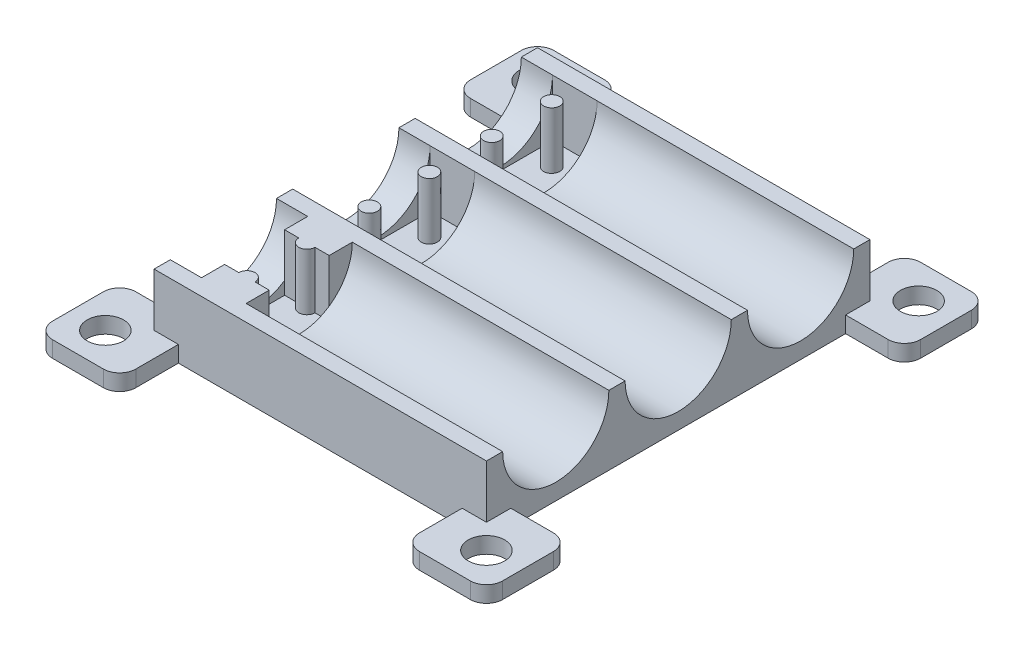
SolidWorks part; units mm, degrees
ref_plane "Front Plane" through (0, 0, 0) normal (0, 0, 1) x (1, 0, 0)
ref_plane "Top Plane" through (0, 0, 0) normal (0, 1, 0) x (1, 0, 0)
ref_plane "Right Plane" through (0, 0, 0) normal (1, 0, 0) x (0, 0, -1)
sketch "Sketch1" plane through (0, 0, 0) normal (1, 0, 0) x (0, 0, -1)
  line L0 (-8.55, 0) -> (-6.55, 0)
  line L1 (-6.55, 0) -> (6.55, 0) construction
  line L2 (6.55, 0) -> (8.55, 0)
  line L3 (-21.65, 0) -> (-8.55, 0) construction
  line L4 (8.55, 0) -> (21.65, 0) construction
  line L5 (-21.65, 0) -> (-23.65, 0)
  line L6 (-23.65, 0) -> (-23.65, -8.55)
  line L7 (-23.65, -8.55) -> (23.65, -8.55)
  line L8 (23.65, -8.55) -> (23.65, 0)
  line L9 (23.65, 0) -> (21.65, 0)
  line L10 (0, -6.55) -> (0, -8.55) construction
  arc A0 (-6.55, 0) -> (6.55, 0) centre (0, 0) ccw
  arc A1 (-21.65, 0) -> (-8.55, 0) centre (-15.1, 0) ccw
  arc A2 (8.55, 0) -> (21.65, 0) centre (15.1, 0) ccw
  dimension "D1" = 13.1
  dimension "D2" = 2
extrude "Boss-Extrude1" add sketch "Sketch1" along normal blind 41
sketch "Sketch2" plane through (0, 0, 0) normal (0, 1, 0) x (1, 0, 0)
  line L0 (6.6, -3.7) -> (6.6, 3.7) construction
  line L1 (5.6, -3.7) -> (5.6, 3.7) construction
  line L2 (0, -7.55) -> (41, -7.55) construction
  line L3 (0, -6.55) -> (0, -8.55) construction
  line L4 (41, -6.55) -> (41, -8.55) construction
  line L5 (0, 7.55) -> (41, 7.55) construction
  line L6 (0, 8.55) -> (0, 6.55) construction
  line L7 (41, 8.55) -> (41, 6.55) construction
  circle A2 centre (6.6, 3.7) radius 1
  circle A3 centre (6.6, -3.7) radius 1
  circle A4 centre (6.6, -11.4) radius 1
  circle A5 centre (6.6, -18.8) radius 1
  circle A6 centre (6.6, 18.8) radius 1
  circle A7 centre (6.6, 11.4) radius 1
  point P4 (6.6, 0)
  point P20 (0, 7.55)
  dimension "D2" = 2
  dimension "D1" = 5.6
  dimension "D3" = 7.4
extrude "Boss-Extrude2" add sketch "Sketch2" against normal up to next
sketch "Sketch4" plane through (0, 0, 0) normal (0, 1, 0) x (1, 0, 0)
  line L0 (41, -6.55) -> (0, -6.55) construction
  line L1 (3.85, -6.55) -> (9.35, -6.55)
  line L2 (3.85, -6.55) -> (3.85, 6.55)
  line L3 (3.85, 6.55) -> (9.35, 6.55)
  line L4 (9.35, -6.55) -> (9.35, 6.55)
  line L5 (41, 6.55) -> (0, 6.55) construction
  line L6 (6.6, -3.7) -> (6.6, 3.7) construction
  line L7 (9.35, 0) -> (3.85, 0) construction
  line L8 (0, -7.55) -> (41, -7.55) construction
  line L9 (0, -6.55) -> (0, -8.55) construction
  line L10 (41, -6.55) -> (41, -8.55) construction
  line L11 (0, 7.55) -> (41, 7.55) construction
  line L12 (0, 8.55) -> (0, 6.55) construction
  line L13 (41, 8.55) -> (41, 6.55) construction
  line L14 (3.85, -21.65) -> (9.35, -21.65)
  line L15 (9.35, -8.55) -> (9.35, -21.65)
  line L16 (3.85, -8.55) -> (9.35, -8.55)
  line L17 (3.85, -8.55) -> (3.85, -21.65)
  line L18 (3.85, 8.55) -> (9.35, 8.55)
  line L19 (9.35, 21.65) -> (9.35, 8.55)
  line L20 (3.85, 21.65) -> (9.35, 21.65)
  line L21 (3.85, 21.65) -> (3.85, 8.55)
  circle A0 centre (6.6, 3.7) radius 1 construction
  circle A1 centre (6.6, -3.7) radius 1 construction
  circle A2 centre (6.6, 3.7) radius 1
  circle A3 centre (6.6, -3.7) radius 1
  circle A4 centre (6.6, -11.4) radius 1
  circle A5 centre (6.6, -18.8) radius 1
  circle A6 centre (6.6, 11.4) radius 1
  circle A7 centre (6.6, 18.8) radius 1
  point P16 (6.6, 0)
  point P17 (6.6, 0)
  dimension "D1" = 5.5
extrude "Cut-Extrude1" cut sketch "Sketch4" against normal blind 7
sketch "Sketch5" plane through (0, -8.55, 0) normal (0, -1, 0) x (1, 0, 0)
  line L0 (0, 23.65) -> (0, 20.65)
  line L1 (-5.2552, 30.9052) -> (1, 30.9052)
  line L2 (-7.2552, 28.9052) -> (-7.2552, 22.65)
  line L3 (-5.2552, 20.65) -> (0, 20.65)
  line L12 (3, 28.9052) -> (3, 23.65)
  line L14 (0, 23.65) -> (3, 23.65)
  line L16 (0, 23.65) -> (-7.2552, 30.9052) construction
  line L17 (-3.0052, 28.9052) -> (-3.0052, 30.9052) construction
  line L18 (-1.4142, 25.0642) -> (0, 23.65) construction
  line L19 (0, 0) -> (41, 0) construction
  line L20 (41, 23.65) -> (41, -23.65) construction
  line L21 (-1.4142, -25.0642) -> (0, -23.65) construction
  line L22 (-3.0052, -28.9052) -> (-3.0052, -30.9052) construction
  line L23 (0, -23.65) -> (-7.2552, -30.9052) construction
  line L24 (0, -23.65) -> (3, -23.65)
  line L25 (3, -28.9052) -> (3, -23.65)
  line L26 (-5.2552, -20.65) -> (0, -20.65)
  line L27 (-7.2552, -28.9052) -> (-7.2552, -22.65)
  line L28 (-5.2552, -30.9052) -> (1, -30.9052)
  line L29 (0, -23.65) -> (0, -20.65)
  line L30 (20.5, 23.65) -> (20.5, -23.65) construction
  line L31 (41, 23.65) -> (0, 23.65) construction
  line L32 (41, -23.65) -> (0, -23.65) construction
  line L33 (41, -23.65) -> (48.2552, -30.9052) construction
  line L34 (44.0052, -28.9052) -> (44.0052, -30.9052) construction
  line L35 (42.4142, -25.0642) -> (41, -23.65) construction
  line L36 (42.4142, 25.0642) -> (41, 23.65) construction
  line L37 (44.0052, 28.9052) -> (44.0052, 30.9052) construction
  line L38 (41, 23.65) -> (48.2552, 30.9052) construction
  line L39 (41, -23.65) -> (41, -20.65)
  line L40 (46.2552, -30.9052) -> (40, -30.9052)
  line L41 (48.2552, -28.9052) -> (48.2552, -22.65)
  line L42 (46.2552, -20.65) -> (41, -20.65)
  line L43 (38, -28.9052) -> (38, -23.65)
  line L44 (41, -23.65) -> (38, -23.65)
  line L45 (41, 23.65) -> (38, 23.65)
  line L46 (38, 28.9052) -> (38, 23.65)
  line L47 (46.2552, 20.65) -> (41, 20.65)
  line L48 (48.2552, 28.9052) -> (48.2552, 22.65)
  line L49 (46.2552, 30.9052) -> (40, 30.9052)
  line L50 (41, 23.65) -> (41, 20.65)
  circle A0 centre (-3.0052, 26.6552) radius 2.25
  arc A1 (-7.2552, 22.65) -> (-5.2552, 20.65) centre (-5.2552, 22.65) ccw
  arc A2 (-5.2552, 30.9052) -> (-7.2552, 28.9052) centre (-5.2552, 28.9052) ccw
  arc A3 (1, 30.9052) -> (3, 28.9052) centre (1, 28.9052) cw
  arc A4 (1, -30.9052) -> (3, -28.9052) centre (1, -28.9052) ccw
  arc A5 (-5.2552, -30.9052) -> (-7.2552, -28.9052) centre (-5.2552, -28.9052) cw
  arc A6 (-7.2552, -22.65) -> (-5.2552, -20.65) centre (-5.2552, -22.65) cw
  circle A7 centre (-3.0052, -26.6552) radius 2.25
  circle A8 centre (44.0052, -26.6552) radius 2.25
  arc A9 (48.2552, -22.65) -> (46.2552, -20.65) centre (46.2552, -22.65) ccw
  arc A10 (46.2552, -30.9052) -> (48.2552, -28.9052) centre (46.2552, -28.9052) ccw
  arc A11 (40, -30.9052) -> (38, -28.9052) centre (40, -28.9052) cw
  arc A12 (40, 30.9052) -> (38, 28.9052) centre (40, 28.9052) ccw
  arc A13 (46.2552, 30.9052) -> (48.2552, 28.9052) centre (46.2552, 28.9052) cw
  arc A14 (48.2552, 22.65) -> (46.2552, 20.65) centre (46.2552, 22.65) cw
  circle A15 centre (44.0052, 26.6552) radius 2.25
  dimension "D1" = 4.5
  dimension "D4" = 2
  dimension "D5" = 2
  dimension "D2" = 3
  dimension "D3" = 2
extrude "Boss-Extrude3" add sketch "Sketch5" against normal blind 2
sketch "Sketch6" plane through (0, 0, 0) normal (0, 1, 0) x (1, 0, 0)
  line L0 (0, 0) -> (41, 0) construction
  line L1 (3.85, -3.7) -> (9.35, -3.7)
  line L2 (9.35, -3.7) -> (9.35, -6.55)
  line L3 (9.35, -6.55) -> (3.85, -6.55)
  line L4 (3.85, -6.55) -> (3.85, -3.7)
  line L5 (7.6, -3.7) -> (5.6, -3.7) construction
  line L6 (7.6, 3.7) -> (5.6, 3.7) construction
  line L7 (3.85, 6.55) -> (3.85, 3.7)
  line L8 (9.35, 6.55) -> (3.85, 6.55)
  line L9 (9.35, 3.7) -> (9.35, 6.55)
  line L10 (3.85, 3.7) -> (9.35, 3.7)
  line L11 (0, -7.55) -> (41, -7.55) construction
  line L12 (0, 7.55) -> (41, 7.55) construction
  line L13 (0, -6.55) -> (0, -8.55) construction
  line L14 (0, 8.55) -> (0, 6.55) construction
  line L15 (41, 8.55) -> (41, 6.55) construction
  line L16 (41, -6.55) -> (41, 6.55) construction
  line L17 (41, -6.55) -> (41, -8.55) construction
  line L18 (9.35, -6.55) -> (9.35, 6.55) construction
  line L19 (5.6, -3.7) -> (7.6, -3.7) construction
  line L20 (5.6, -11.4) -> (7.6, -11.4) construction
  line L21 (7.6, -18.8) -> (5.6, -18.8) construction
  line L22 (7.6, -11.4) -> (5.6, -11.4) construction
  line L23 (3.85, -18.8) -> (9.35, -18.8)
  line L24 (9.35, -18.8) -> (9.35, -21.65)
  line L25 (9.35, -21.65) -> (3.85, -21.65)
  line L26 (3.85, -21.65) -> (3.85, -18.8)
  line L27 (3.85, -8.55) -> (3.85, -11.4)
  line L28 (9.35, -8.55) -> (3.85, -8.55)
  line L29 (9.35, -11.4) -> (9.35, -8.55)
  line L30 (3.85, -11.4) -> (9.35, -11.4)
  line L31 (5.6, 18.8) -> (7.6, 18.8) construction
  line L32 (7.6, 11.4) -> (5.6, 11.4) construction
  line L33 (7.6, 18.8) -> (5.6, 18.8) construction
  line L34 (3.85, 11.4) -> (9.35, 11.4)
  line L35 (9.35, 11.4) -> (9.35, 8.55)
  line L36 (9.35, 8.55) -> (3.85, 8.55)
  line L37 (3.85, 8.55) -> (3.85, 11.4)
  line L38 (3.85, 21.65) -> (3.85, 18.8)
  line L39 (9.35, 21.65) -> (3.85, 21.65)
  line L40 (9.35, 18.8) -> (9.35, 21.65)
  line L41 (3.85, 18.8) -> (9.35, 18.8)
  circle A0 centre (6.6, -3.7) radius 1 construction
  circle A1 centre (6.6, -3.7) radius 1 construction
extrude "Boss-Extrude4" add sketch "Sketch6" against normal up to surface (7 mm away) up to face at (6.6, -7, -19.8)
sketch "Sketch7" plane through (0, 0, 0) normal (0, 1, 0) x (1, 0, 0)
  line L0 (5.6, 3.7) -> (3.85, 3.7)
  line L1 (3.85, 3.7) -> (3.85, 6.55)
  line L2 (3.85, 6.55) -> (9.35, 6.55)
  line L3 (9.35, 6.55) -> (9.35, 3.7)
  line L4 (7.6, 3.7) -> (9.35, 3.7) construction
  line L5 (7.6, 3.7) -> (9.35, 3.7)
  line L6 (0, 0) -> (41, 0) construction
  line L7 (41, -6.55) -> (41, 6.55) construction
  line L8 (7.6, -3.7) -> (9.35, -3.7)
  line L9 (9.35, -6.55) -> (9.35, -3.7)
  line L10 (3.85, -6.55) -> (9.35, -6.55)
  line L11 (3.85, -3.7) -> (3.85, -6.55)
  line L12 (5.6, -3.7) -> (3.85, -3.7)
  line L13 (0, 7.55) -> (41, 7.55) construction
  line L14 (0, 8.55) -> (0, 6.55) construction
  line L15 (41, 8.55) -> (41, 6.55) construction
  line L16 (5.6, 18.8) -> (3.85, 18.8)
  line L17 (3.85, 18.8) -> (3.85, 21.65)
  line L18 (3.85, 21.65) -> (9.35, 21.65)
  line L19 (9.35, 21.65) -> (9.35, 18.8)
  line L20 (7.6, 18.8) -> (9.35, 18.8)
  line L21 (7.6, 11.4) -> (9.35, 11.4)
  line L22 (9.35, 8.55) -> (9.35, 11.4)
  line L23 (3.85, 8.55) -> (9.35, 8.55)
  line L24 (3.85, 11.4) -> (3.85, 8.55)
  line L25 (5.6, 11.4) -> (3.85, 11.4)
  arc A0 (7.6, 3.7) -> (5.6, 3.7) centre (6.6, 3.7) ccw
  arc A1 (5.6, 3.7) -> (7.6, 3.7) centre (6.6, 3.7) ccw construction
  arc A2 (7.6, -3.7) -> (5.6, -3.7) centre (6.6, -3.7) cw
  arc A3 (7.6, 18.8) -> (5.6, 18.8) centre (6.6, 18.8) ccw
  arc A4 (7.6, 11.4) -> (5.6, 11.4) centre (6.6, 11.4) cw
extrude "Cut-Extrude2" cut sketch "Sketch7" against normal up to surface (7 mm away) up to face at (6.6, -7, -15.1)
